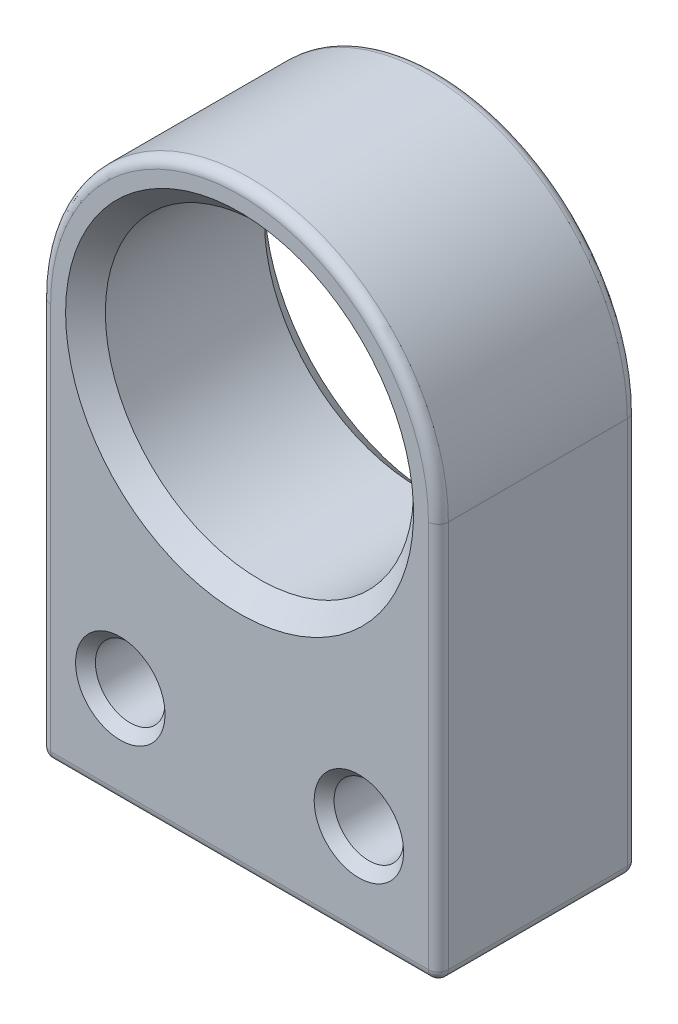
SolidWorks part; units mm, degrees
ref_plane "前视基准面" through (0, 0, 0) normal (0, 0, 1) x (1, 0, 0)
ref_plane "上视基准面" through (0, 0, 0) normal (0, 1, 0) x (1, 0, 0)
ref_plane "右视基准面" through (0, 0, 0) normal (1, 0, 0) x (0, 0, -1)
sketch "草图1" plane through (0, 0, 0) normal (0, 0, 1) x (1, 0, 0)
  line L0 (-6, 0) -> (6, 0) construction
  line L1 (-10, -5) -> (10, -5)
  line L2 (-10, -5) -> (-10, 5)
  line L3 (-10, 5) -> (10, 5)
  line L4 (10, -5) -> (10, 5)
  line L5 (-10, -5) -> (10, 5) construction
  line L6 (-10, 5) -> (10, -5) construction
  circle A0 centre (-6, 0) radius 1.75
  circle A1 centre (6, 0) radius 1.75
  point P0 (0, 0)
  point P9 (0, 0)
  dimension "D4" = 3.5
  dimension "D1" = 20
  dimension "D2" = 10
  dimension "D3" = 12
extrude "凸台-拉伸1" add sketch "草图1" along normal blind 10
sketch "草图2" plane through (0, 0, 10) normal (0, 0, 1) x (1, 0, 0)
  line L0 (10, 5) -> (-10, 5) construction
  line L1 (-10, 5) -> (10, 5)
  line L2 (10, 5) -> (10, 15)
  line L3 (-10, 5) -> (-10, 15)
  circle A0 centre (0, 15) radius 10
  circle A1 centre (0, 15) radius 7.75
  line M3 (10, 5) -> (-10, 5)
  dimension "D1" = 20
  dimension "D2" = 15.5
extrude "凸台-拉伸2" add sketch "草图2" against normal blind 10 contours A0 L3 L1 | A0 | A0 L2 M3
chamfer "倒角1" distance 1 angle 45 2 edges at (7.75, 15, 0) (7.75, 15, 10)
chamfer "倒角2" distance 0.5 angle 45 4 edges at (7.75, 0, 10) (7.75, 0, 0) (-4.25, 0, 10) (-4.25, 0, 0)
fillet "圆角1" radius 0.5 10 edges at (10, 5, 0) (10, 5, 10) (0, 25, 10) (0, 25, 0) (0, -5, 0) (0, -5, 10) (10, -5, 5) (-10, 5, 0) (-10, 5, 10) (-10, -5, 5)
